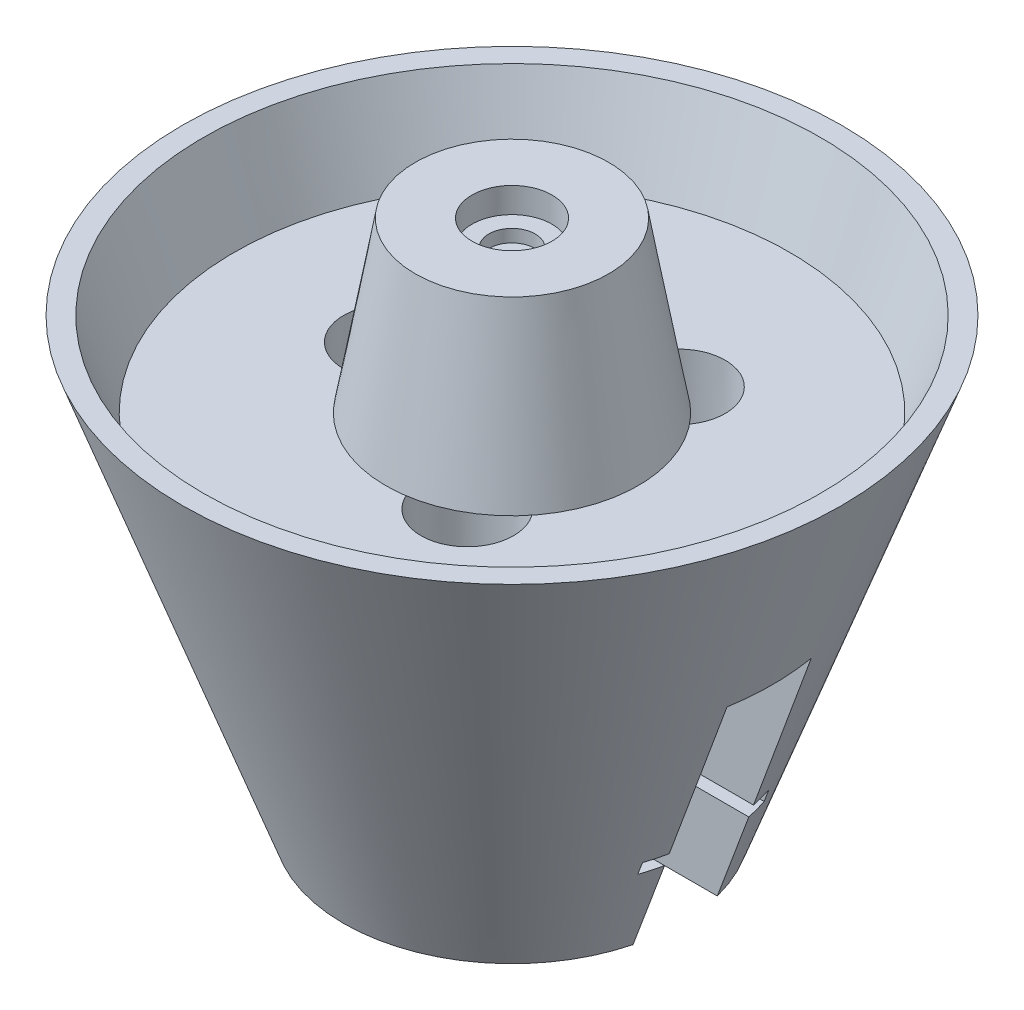
SolidWorks part; units mm, degrees
ref_plane "Front Plane" through (0, 0, 0) normal (0, 0, 1) x (1, 0, 0)
ref_plane "Top Plane" through (0, 0, 0) normal (0, 1, 0) x (1, 0, 0)
ref_plane "Right Plane" through (0, 0, 0) normal (1, 0, 0) x (0, 0, -1)
sketch "Sketch1" plane through (0, 0, 0) normal (0, 1, 0) x (1, 0, 0)
  circle A1 centre (0, 0) radius 40
  dimension "D1" = 80
extrude "Boss-Extrude1" add sketch "Sketch1" along normal blind 105 draft 20 draft outward yes
sketch "Sketch2" plane through (0, 0, 0) normal (0, -1, 0) x (1, 0, 0)
  circle A0 centre (0, 0) radius 10
  dimension "D1" = 20
extrude "Cut-Extrude1" cut sketch "Sketch2" against normal blind 20
sketch "Sketch3" plane through (0, 0, 0) normal (0, 0, 1) x (1, 0, 0)
  line L0 (0, 0) -> (0, 60)
  line L1 (0, 60) -> (90.1528, 60)
  line L2 (90.1528, 60) -> (90.1528, 0)
  line L3 (90.1528, 0) -> (0, 0)
  dimension "D1" = 60
extrude "Cut-Extrude2" cut sketch "Sketch3" against normal mid plane 20
sketch "Sketch4" plane through (0, 0, 0) normal (0, -1, 0) x (1, 0, 0)
  line L0 (14.5, 25.1147) -> (0, 0) construction
  line L1 (0, 0) -> (42.2856, 0) construction
  circle A6 centre (14.5, 25.1147) radius 9.5
  circle A11 centre (-29, 0) radius 9.5
  circle A12 centre (14.5, -25.1147) radius 9.5
  point P10 (0, 0)
  point P15 (0, 0)
  dimension "D1" = 19
  dimension "D2" = 60
  dimension "D5" = 19
  dimension "D3" = 29
  dimension "D4" = 29
extrude "Cut-Extrude3" cut sketch "Sketch4" against normal up to surface (105 mm away) draft 1
ref_plane "Plane1" through (0, 20, 0) normal (0, -1, 0) x (-1, 0, 0)
sketch "Sketch7" plane through (0, 20, 0) normal (0, -1, 0) x (1, 0, 0)
  circle A0 centre (0, 0) radius 17.5
  dimension "D1" = 35
extrude "Cut-Extrude5" cut sketch "Sketch7" against normal blind 80
sketch "Sketch8" plane through (0, 20, 0) normal (0, 1, 0) x (1, 0, 0)
  line L1 (0, -15) -> (73.5402, -15)
  line L2 (0, 10) -> (14.3614, 10)
  line L3 (14.3614, -10) -> (0, -10)
  line L4 (0, 10) -> (14.3614, 10)
  line L5 (14.3614, -10) -> (0, -10)
  line L6 (0, -15) -> (0, 15)
  line L7 (0, 15) -> (73.5402, 15)
  line L8 (73.5402, -15) -> (73.5402, 15)
  arc A2 (14.3614, 10) -> (14.3614, -10) centre (0, 0) ccw
  arc A3 (0, 10) -> (0, -10) centre (0, 0) ccw
  arc A4 (14.3614, 10) -> (14.3614, -10) centre (0, 0) ccw
  arc A5 (0, 10) -> (0, -10) centre (0, 0) ccw
  line M7 (0, 10) -> (14.3614, 10)
  arc M8 (14.3614, 10) -> (14.3614, -10) centre (0, 0) ccw
  line M9 (14.3614, -10) -> (0, -10)
  dimension "D2" = 5
  dimension "D3" = 5
  dimension "D1" = 0
extrude "Cut-Extrude6" cut sketch "Sketch8" along normal blind 3 contours L1 L8 L7 L6 M8 M7 M9 | L7 L6 M7 M8 | L6 L1 M8 M9
sketch "Sketch9" plane through (0, 105, 0) normal (0, 1, 0) x (1, 0, 0)
  circle A0 centre (0, 0) radius 73.2169
  circle A1 centre (0, 0) radius 78.2169 construction
  dimension "D1" = 5
extrude "Cut-Extrude7" cut sketch "Sketch9" against normal mid plane 40 draft 20
sketch "Sketch10" plane through (0, 85, 0) normal (0, 1, 0) x (1, 0, 0)
  circle A0 centre (0, 0) radius 30
  dimension "D1" = 60
extrude "Boss-Extrude2" add sketch "Sketch10" along normal blind 40 draft 10 separate body
sketch "Sketch11" plane through (0, 125, 0) normal (0, 1, 0) x (1, 0, 0)
  circle A0 centre (0, 0) radius 9.5
  dimension "D1" = 19
extrude "Cut-Extrude8" cut sketch "Sketch11" against normal blind 6
sketch "Sketch12" plane through (0, 119, 0) normal (0, 1, 0) x (1, 0, 0)
  circle A0 centre (0, 0) radius 5.5
  dimension "D1" = 11
extrude "Cut-Extrude9" cut sketch "Sketch12" against normal blind 3
